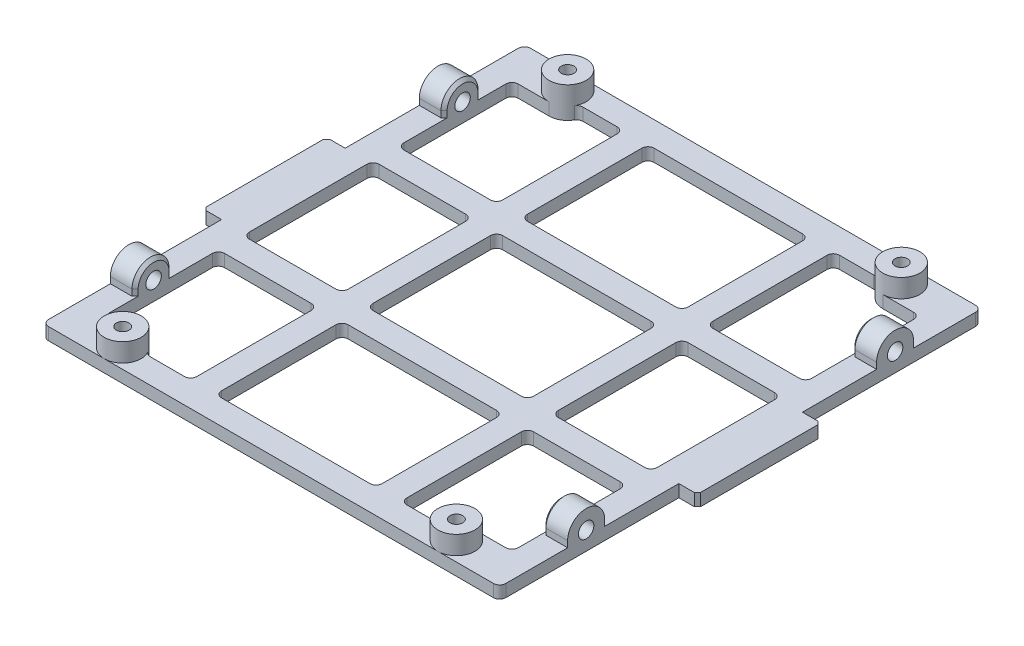
SolidWorks part; units mm, degrees
material "6061 合金"
ref_plane "前视基准面" through (0, 0, 0) normal (0, 0, 1) x (1, 0, 0)
ref_plane "上视基准面" through (0, 0, 0) normal (0, 1, 0) x (1, 0, 0)
ref_plane "右视基准面" through (0, 0, 0) normal (1, 0, 0) x (0, 0, -1)
sketch "草图1" plane through (0, 0, 0) normal (0, 0, 1) x (1, 0, 0)
  line L0 (-40, 0) -> (-40, 2)
  line L1 (-40, 2) -> (-37, 2)
  line L2 (-37, 2) -> (-37, 6)
  line L3 (-37, 6) -> (-33, 6)
  line L4 (-33, 6) -> (-33, 2)
  line L5 (-33, 2) -> (33, 2)
  line L6 (-40, 0) -> (40, 0)
  line L7 (0, -55) -> (0, 55) construction
  line L8 (33, 6) -> (33, 2)
  line L9 (37, 6) -> (33, 6)
  line L10 (37, 2) -> (37, 6)
  line L11 (40, 2) -> (37, 2)
  line L12 (40, 0) -> (40, 2)
  dimension "D1" = 4
  dimension "D2" = 2
  dimension "D3" = 3
  dimension "D4" = 74
  dimension "D5" = 6
extrude "凸台-拉伸1" add sketch "草图1" along normal mid plane 78
sketch "草图2" plane through (0, 2, 0) normal (0, 1, 0) x (1, 0, 0)
  line L0 (-37, -39) -> (-37, 39) construction
  line L3 (-40, 10) -> (-37, 10)
  line L5 (-3.3, 0) -> (3.3, 0) construction
  line L10 (-24.1716, -35) -> (24.1716, -35)
  line L12 (-40, -10) -> (-37, -10)
  line L15 (0, -3.3) -> (0, 3.3) construction
  line L18 (40, -10) -> (37, -10)
  line L20 (-40, -39) -> (-40, 39) construction
  line L22 (40, 10) -> (37, 10)
  line L41 (27, -33) -> (33, -33)
  line L42 (27, 33) -> (33, 33)
  line L47 (33, 33) -> (33, -33)
  line L48 (-37, 10) -> (-37, 39)
  line L49 (-24.1716, 35) -> (24.1716, 35)
  line L50 (-37, -10) -> (-37, -39)
  line L52 (37, 10) -> (37, 39)
  line L53 (37, -10) -> (37, -39)
  line L54 (-40, 10) -> (-40, 39)
  line L55 (-40, 39) -> (-37, 39)
  line L56 (-40, -10) -> (-40, -39)
  line L57 (-40, -39) -> (-37, -39)
  line L58 (-27, 33) -> (-33, 33)
  line L59 (-33, -39) -> (-33, 39) construction
  line L60 (33, 39) -> (-33, 39) construction
  line L61 (-33, 33) -> (-33, -33)
  line L62 (-27, -33) -> (-33, -33)
  line L63 (40, -39) -> (37, -39)
  line L64 (40, -10) -> (40, -39)
  line L65 (40, 10) -> (40, 39)
  line L66 (40, 39) -> (37, 39)
  arc A0 (-27, 33) -> (-24.1716, 35) centre (-27, 36) ccw
  arc A8 (-27, -33) -> (-24.1716, -35) centre (-27, -36) cw
  arc A9 (27, -33) -> (24.1716, -35) centre (27, -36) ccw
  arc A10 (27, 33) -> (24.1716, 35) centre (27, 36) cw
  dimension "D8" = 6
  dimension "D2" = 72
  dimension "D4" = 4
  dimension "D1" = 54
  dimension "D3" = 20
extrude "切除-拉伸1" cut sketch "草图2" against normal through all
sketch "草图3" plane through (0, 0, 0) normal (1, 0, 0) x (0, 0, -1)
  line L1 (-39, 6) -> (39, 6) construction
  line L3 (-22, 2) -> (22, 2)
  line L4 (-10, 2) -> (10, 2) construction
  line L5 (-28, 2) -> (-39, 2)
  line L6 (-39, 7) -> (39, 7)
  line L7 (0, 3.3) -> (0, -3.3) construction
  line L10 (-39, 0) -> (-39, 6) construction
  line L11 (-39, 2) -> (-39, 7)
  line L12 (39, 2) -> (39, 7)
  line L13 (28, 2) -> (39, 2)
  line L14 (-28, 2) -> (-28, 3)
  line L15 (-22, 2) -> (-22, 3)
  line L17 (22, 2) -> (22, 3)
  line L18 (28, 2) -> (28, 3)
  arc A0 (-22, 3) -> (-28, 3) centre (-25, 3) ccw
  arc A1 (22, 3) -> (28, 3) centre (25, 3) cw
  dimension "D1" = 6
  dimension "D2" = 1
  dimension "D3" = 50
extrude "切除-拉伸2" cut sketch "草图3" against normal through all both and the other way through all
sketch "草图4" plane through (0, 2, 0) normal (0, 1, 0) x (1, 0, 0)
  line L0 (-3.3, 0) -> (3.3, 0) construction
  line L1 (0, -3.3) -> (0, 3.3) construction
  circle A0 centre (-27, 36) radius 3
  circle A1 centre (-27, -36) radius 3
  circle A2 centre (27, -36) radius 3
  circle A3 centre (27, 36) radius 3
  dimension "D1" = 6
extrude "凸台-拉伸2" add sketch "草图4" along normal blind 3
hole_wizard "M3 螺纹孔1" positions "草图5" profile "草图6" tap size "M3" standard "GB"
sketch "草图5" plane through (-37, 0, 0) normal (-1, 0, 0) x (0, 0, 1)
  point P0 (-25, 3)
  point P3 (25, 3)
cosmetic thread "孔螺蚊线1" parameters "D2"=3
cosmetic thread "孔螺蚊线2" parameters "D2"=3
sketch "草图6" plane through (-37, 3, -25) normal (0, 1, 0) x (0, 0, 1)
  line L0 (0, 0) -> (0, 74)
  line L1 (0, 74) -> (1.25, 74)
  line L2 (1.25, 74) -> (1.25, 0)
  line L5 (1.25, 0) -> (0, 0)
  line L11 (0, -6.35) -> (0, 107.95) construction
  dimension "通孔螺纹孔钻头直径" = 2.5
  dimension "通孔螺纹孔钻头深度" = 74
hole_wizard "M2.5 螺纹孔1" positions "草图7" profile "草图8" tap size "M2.5" standard "GB" end condition through all
sketch "草图7" plane through (0, 5, 0) normal (0, 1, 0) x (1, 0, 0)
  point P0 (-27, 36)
  point P3 (27, 36)
  point P6 (-27, -36)
  point P9 (27, -36)
sketch "草图8" plane through (-27, 5, -36) normal (1, 0, 0) x (0, 0, 1)
  line L0 (0, 0) -> (0, 5)
  line L1 (0, 5) -> (1.025, 5)
  line L2 (1.025, 5) -> (1.025, 0)
  line L5 (1.025, 0) -> (0, 0)
  line L11 (0, -6.35) -> (0, 107.95) construction
  dimension "通孔螺纹孔钻头直径" = 2.05
  dimension "通孔螺纹孔钻头深度" = 5
cosmetic thread "孔螺蚊线3" parameters "D2"=2.5
cosmetic thread "孔螺蚊线4" parameters "D2"=2.5
cosmetic thread "孔螺蚊线5" parameters "D2"=2.5
cosmetic thread "孔螺蚊线6" parameters "D2"=2.5
mirror "镜向1" about plane through (0, 0, 0) normal (1, 0, 0) of "M3 螺纹孔1"
sketch "草图9" [suppressed] plane through (0, 2, 0) normal (0, 1, 0) x (1, 0, 0)
  line L0 (-33, 36.3025) -> (-33, 2)
  line L1 (-33, 22) -> (-33, 28) construction
  line L2 (-21.0762, 35) -> (-2, 35)
  line L3 (27, 39) -> (-27, 39) construction
  line L4 (-33, 2) -> (-2, 2)
  line L5 (-2, 2) -> (-2, 35)
  line L6 (0, -3.3) -> (0, 3.3) construction
  line L7 (2, 2) -> (2, 35)
  line L8 (33, 2) -> (2, 2)
  line L9 (21.0762, 35) -> (2, 35)
  line L10 (33, 36.3025) -> (33, 2)
  line L11 (-3.3, 0) -> (3.3, 0) construction
  line L12 (33, -36.3025) -> (33, -2)
  line L13 (21.0762, -35) -> (2, -35)
  line L14 (33, -2) -> (2, -2)
  line L15 (2, -2) -> (2, -35)
  line L16 (-2, -2) -> (-2, -35)
  line L17 (-33, -2) -> (-2, -2)
  line L18 (-21.0762, -35) -> (-2, -35)
  line L19 (-33, -36.3025) -> (-33, -2)
  arc A2 (33, 36.3025) -> (21.0762, 35) centre (27, 36) cw
  arc A3 (-33, 36.3025) -> (-21.0762, 35) centre (-27, 36) ccw
  arc A4 (-33, -36.3025) -> (-21.0762, -35) centre (-27, -36) cw
  arc A5 (33, -36.3025) -> (21.0762, -35) centre (27, -36) ccw
  dimension "D2" = 4
  dimension "D3" = 4
  dimension "D4" = 4
chamfer "倒角1" distance 0.5 angle 45 16 edges at (-33, 2.5, -28) (-33, 2.5, -22) (-33, 6, -25) (33, 2.5, -22) (33, 2.5, -28) (33, 6, -25) (-33, 2.5, 22) (-33, 2.5, 28) (-33, 6, 25) (33, 2.5, 28) (33, 2.5, 22) (33, 6, 25) (40, 1, 10) (40, 1, -10) (-40, 1, 10) (-40, 1, -10)
sketch "草图10" plane through (0, 2, 0) normal (0, 1, 0) x (1, 0, 0)
  line L0 (-15, 35) -> (-15, -35)
  line L1 (24.1716, 35) -> (-24.1716, 35) construction
  line L2 (-24.1716, -35) -> (24.1716, -35) construction
  line L3 (-33, 12.5) -> (33, 12.5)
  line L4 (-33, 22.5) -> (-33, -22.5) construction
  line L5 (33, -22.5) -> (33, 22.5) construction
  line L6 (-3.3, 0) -> (3.3, 0) construction
  line L7 (-33, -12.5) -> (33, -12.5)
  line L8 (0, -3.3) -> (0, 3.3) construction
  line L9 (15, 35) -> (15, -35)
  dimension "D1" = 25
  dimension "D2" = 30
extrude "拉伸-薄壁1" add sketch "草图10" against normal up to surface (2 mm away) thin up to face at (-27, 0, -34.975) thin type mid plane wall 4
fillet "圆角1" radius 1 44 edges at (37, 1, 39) (-37, 1, -39) (-37, 1, 39) (37, 1, -39) (-13, 1, -35) (-13, 1, -10.5) (-17, 1, -14.5) (-17, 1, 10.5) (-13, 1, 35) (-13, 1, 14.5) (-17, 1, -35) (-17, 1, 35) (-33, 1, 14.5) (-33, 1, 10.5) (-17, 1, 14.5) (-33, 1, -10.5) (-17, 1, -10.5) (-33, 1, -14.5) (-13, 1, -14.5) (13, 1, -14.5) (-13, 1, 10.5) (13, 1, 10.5) (17, 1, -10.5) (33, 1, -10.5) (33, 1, -14.5) (13, 1, 14.5) (13, 1, 35) (17, 1, 35) (17, 1, 14.5) (33, 1, 14.5) (33, 1, 10.5) (13, 1, -10.5) (17, 1, 10.5) (17, 1, -14.5) (17, 1, -35) (13, 1, -35) (-24.1716, 1, 35) (-33, 1, 33) (-33, 1, -33) (-24.1716, 1, -35) (24.1716, 1, -35) (33, 1, -33) (33, 1, 33) (24.1716, 1, 35)
